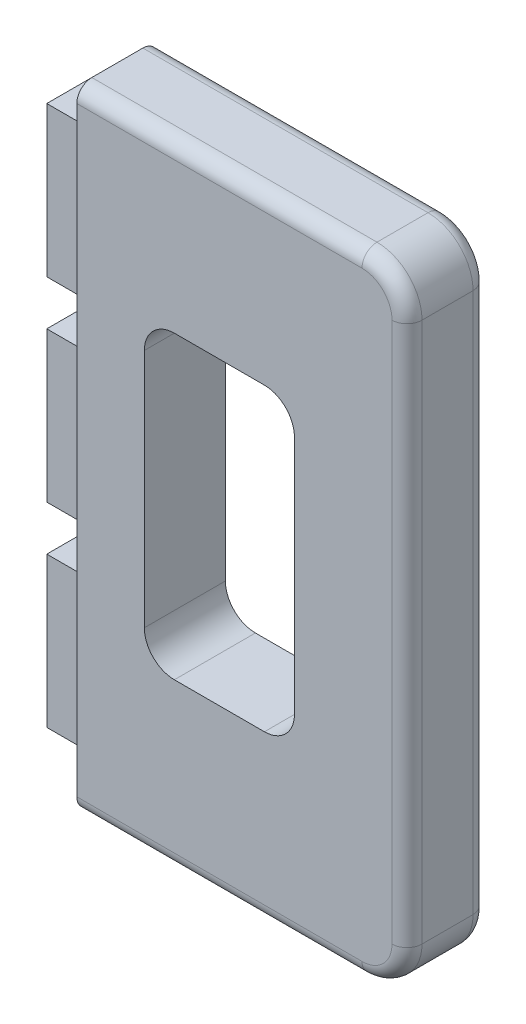
SolidWorks part; units mm, degrees
ref_plane "Front Plane" through (0, 0, 0) normal (0, 0, 1) x (1, 0, 0)
ref_plane "Top Plane" through (0, 0, 0) normal (0, 1, 0) x (1, 0, 0)
ref_plane "Right Plane" through (0, 0, 0) normal (1, 0, 0) x (0, 0, -1)
sketch "Sketch1" plane through (0, 0, 0) normal (0, 0, 1) x (1, 0, 0)
  line L0 (0, -25) -> (0, 25)
  line L1 (0, 25) -> (15, 25)
  line L2 (15, 25) -> (15, 40)
  line L3 (15, 40) -> (0, 40)
  line L4 (0, 40) -> (0, 90)
  line L5 (0, 90) -> (15, 90)
  line L6 (15, 90) -> (15, 105)
  line L7 (15, 105) -> (110, 105)
  line L8 (125, 90) -> (125, -90)
  line L9 (110, -105) -> (15, -105)
  line L10 (15, -105) -> (15, -90)
  line L11 (15, -90) -> (0, -90)
  line L12 (0, -90) -> (0, -40)
  line L13 (0, -40) -> (15, -40)
  line L14 (15, -40) -> (15, -25)
  line L15 (15, -25) -> (0, -25)
  line L16 (37.5, -50) -> (87.5, -50)
  line L17 (87.5, -50) -> (87.5, 50)
  line L18 (87.5, 50) -> (37.5, 50)
  line L19 (37.5, -50) -> (37.5, 50)
  line L20 (62.4658, -50) -> (62.4658, -105) construction
  line L21 (87.5, 9.9668) -> (125, 9.9668) construction
  line L22 (68.0096, 50) -> (68.0096, 105) construction
  line L23 (37.5, 12.2347) -> (0, 12.2347) construction
  arc A0 (110, 105) -> (125, 90) centre (110, 90) cw
  arc A1 (125, -90) -> (110, -105) centre (110, -90) cw
  point P4 (0, 0)
  dimension "D5" = 125
  dimension "D7" = 50
  dimension "D1" = 15
  dimension "D2" = 50
  dimension "D3" = 15
  dimension "D4" = 15
  dimension "D6" = 100
extrude "Boss-Extrude4" add sketch "Sketch1" along normal mid plane 17
sketch "Sketch2" plane through (0, 0, -8.5) normal (0, 0, -1) x (-1, 0, 0)
  line L4 (-110, 105) -> (-15, 105) construction
  line L5 (-15, 105) -> (-15, 90) construction
  line L6 (-15, 40) -> (-15, 25) construction
  line L7 (-15, -25) -> (-15, -40) construction
  line L8 (-15, -90) -> (-15, -105) construction
  line L9 (-15, -105) -> (-110, -105) construction
  line L10 (-125, -90) -> (-125, 90) construction
  line L11 (-87.5, 50) -> (-37.5, 50) construction
  line L12 (-37.5, 50) -> (-37.5, -50) construction
  line L13 (-37.5, -50) -> (-87.5, -50) construction
  line L14 (-87.5, -50) -> (-87.5, 50) construction
  line L15 (-110, 105) -> (-15, 105)
  line L16 (-15, 105) -> (-15, 90)
  line L17 (-15, 40) -> (-15, 25)
  line L18 (-15, -25) -> (-15, -40)
  line L19 (-15, -90) -> (-15, -105)
  line L20 (-15, -105) -> (-110, -105)
  line L21 (-125, -90) -> (-125, 90)
  line L22 (-15, -90) -> (-15, -40)
  line L23 (-15, -25) -> (-15, 25)
  line L24 (-15, 40) -> (-15, 90)
  line L25 (-87.5, 50) -> (-37.5, 50)
  line L26 (-37.5, 50) -> (-37.5, -50)
  line L27 (-37.5, -50) -> (-87.5, -50)
  line L28 (-87.5, -50) -> (-87.5, 50)
  arc A2 (-110, 105) -> (-125, 90) centre (-110, 90) ccw construction
  arc A3 (-125, -90) -> (-110, -105) centre (-110, -90) ccw construction
  arc A6 (-110, 105) -> (-125, 90) centre (-110, 90) ccw
  arc A7 (-125, -90) -> (-110, -105) centre (-110, -90) ccw
extrude "Boss-Extrude5" add sketch "Sketch2" along normal blind 5
sketch "Sketch3" plane through (0, 0, 8.5) normal (0, 0, 1) x (1, 0, 0)
  line L4 (15, -90) -> (15, -105) construction
  line L5 (15, -105) -> (110, -105) construction
  line L6 (125, -90) -> (125, 90) construction
  line L7 (110, 105) -> (15, 105) construction
  line L8 (15, 105) -> (15, 90) construction
  line L9 (37.5, 50) -> (37.5, -50) construction
  line L10 (37.5, -50) -> (87.5, -50) construction
  line L11 (87.5, -50) -> (87.5, 50) construction
  line L12 (87.5, 50) -> (37.5, 50) construction
  line L13 (15, -90) -> (15, -105)
  line L14 (15, -105) -> (110, -105)
  line L15 (125, -90) -> (125, 90)
  line L16 (110, 105) -> (15, 105)
  line L17 (15, 105) -> (15, 90)
  line L18 (15, -25) -> (15, -40) construction
  line L19 (15, 40) -> (15, 25) construction
  line L20 (15, -25) -> (15, -40)
  line L21 (15, 40) -> (15, 25)
  line L22 (15, 90) -> (15, 40)
  line L23 (15, 25) -> (15, -25)
  line L24 (15, -40) -> (15, -90)
  line L25 (37.5, 50) -> (37.5, -50)
  line L26 (37.5, -50) -> (87.5, -50)
  line L27 (87.5, -50) -> (87.5, 50)
  line L28 (87.5, 50) -> (37.5, 50)
  arc A2 (110, -105) -> (125, -90) centre (110, -90) ccw construction
  arc A3 (125, 90) -> (110, 105) centre (110, 90) ccw construction
  arc A6 (110, -105) -> (125, -90) centre (110, -90) ccw
  arc A7 (125, 90) -> (110, 105) centre (110, 90) ccw
extrude "Boss-Extrude6" add sketch "Sketch3" along normal blind 5
fillet "Fillet3" radius 10 4 edges at (37.5, 50, 0) (37.5, -50, 0) (87.5, 50, 0) (87.5, -50, 0)
sketch "Sketch4" plane through (0, 0, -13.5) normal (0, 0, -1) x (-1, 0, 0)
  line L0 (-62.5, -50) -> (-62.5, -60) construction
  line L3 (-77.5, -50) -> (-47.5, -50) construction
  line L6 (-62.5, 50) -> (-62.5, 60) construction
  line L7 (-47.5, 50) -> (-77.5, 50) construction
  dimension "D1" = 10
hole_wizard "M5 Clearance Hole1" positions "3DSketch1" profile "Sketch5" hole size "M5" standard "ANSI Metric"
sketch3d "3DSketch1"
  point P0 (62.5, 60, -13.5)
  point P3 (62.5, -60, -13.5)
sketch "Sketch5" plane through (62.5, 60, -13.5) normal (1, 0, 0) x (0, 1, 0)
  line L0 (0, 0) -> (0, 16.5923)
  line L1 (0, 16.5923) -> (2.65, 15)
  line L2 (2.65, 15) -> (2.65, 0)
  line L5 (2.65, 0) -> (0, 0)
  line L10 (0, 16.5923) -> (-2.65, 15) construction
  line L11 (0, -6.35) -> (0, 107.95) construction
  dimension "Hole Dia." = 5.3
  dimension "Hole Depth" = 15
  dimension "Drill Angle" = 118
fillet "Fillet2" radius 5 10 edges at (62.5, 105, -13.5) (120.6066, 100.6066, -13.5) (62.5, -105, -13.5) (120.6066, -100.6066, -13.5) (62.5, -105, 13.5) (120.6066, -100.6066, 13.5) (125, 0, 13.5) (62.5, 105, 13.5) (125, 0, -13.5) (120.6066, 100.6066, 13.5)
